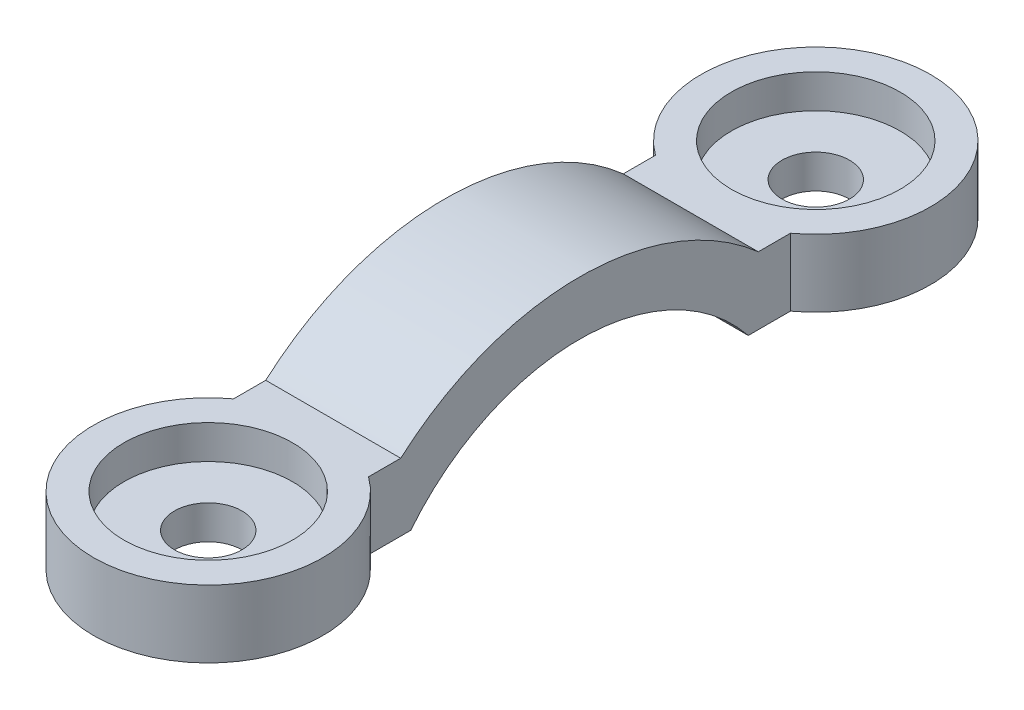
SolidWorks part; units mm, degrees
ref_plane "Plan de face" through (0, 0, 0) normal (0, 0, 1) x (1, 0, 0)
ref_plane "Plan de dessus" through (0, 0, 0) normal (0, 1, 0) x (1, 0, 0)
ref_plane "Plan de droite" through (0, 0, 0) normal (1, 0, 0) x (0, 0, -1)
sketch "Esquisse2" plane through (0, 0, 0) normal (1, 0, 0) x (0, 0, -1)
  line L0 (-16.7178, 10) -> (20.1552, 10) construction
  line L1 (-14.3614, 10) -> (-27.5028, 10)
  line L2 (-27.5028, 10) -> (-27.5028, 15)
  line L3 (-27.5028, 15) -> (-13.2439, 15)
  line L4 (14.3614, 10) -> (22.5028, 10)
  line L5 (27.5028, 15) -> (27.5028, 10)
  line L6 (27.5028, 15) -> (13.2439, 15)
  line L7 (27.5028, 10) -> (22.5028, 10)
  line L8 (-14.3614, 10) -> (-12.5028, 10)
  line L9 (12.5028, 10) -> (22.5028, 10)
  arc A0 (12.5028, 10) -> (-12.5028, 10) centre (0, 0) ccw
  arc A2 (13.2439, 15) -> (-13.2439, 15) centre (0, 0) ccw
  point P5 (-22.5028, 10)
  point P6 (22.5028, 10)
  point P7 (-12.5028, 10)
  point P8 (12.5028, 10)
  dimension "D1" = 32.02
  dimension "D3" = 10
  dimension "D5" = 5
  dimension "D7" = 4
  dimension "D2" = 10
  dimension "D4" = 10
  dimension "D6" = 5
  dimension "D8" = 5
  dimension "D9" = 5
extrude "BASE" add sketch "Esquisse2" along normal blind 10 contours L6 A2 L3 L2 L1 L8 A0 L9 L4 L7 L5
sketch "Esquisse5" plane through (0, 10, 0) normal (0, -1, 0) x (1, 0, 0)
  line L0 (5, 27.5028) -> (5, 12.5028) construction
  line L1 (10, 27.5028) -> (0, 27.5028) construction
  line L2 (10, 12.5028) -> (0, 12.5028) construction
  line L3 (-3.4429, 0) -> (13.3559, 0) construction
  circle A0 centre (5, 22.5028) radius 2.5
  circle A1 centre (5, -22.5028) radius 2.5
  dimension "D2" = 5
  dimension "D1" = 5
extrude "VIDE ACCES VIS" cut sketch "Esquisse5" against normal through all
sketch "Esquisse6" plane through (0, 15, 0) normal (0, 1, 0) x (1, 0, 0)
  circle A0 centre (5, 22.5028) radius 8.5
  circle A1 centre (5, -22.5028) radius 8.5
  circle A2 centre (5, 22.5028) radius 2.5874
  circle A3 centre (5, -22.5028) radius 2.5
  dimension "D1" = 17
  dimension "D2" = 17
extrude "BOSS VIS" add sketch "Esquisse6" against normal up to surface (5 mm away) up to face at (5, 10, -20.0028)
sketch "Esquisse7" plane through (0, 15, 0) normal (0, 1, 0) x (1, 0, 0)
  circle A0 centre (5, 22.5028) radius 6.25
  circle A1 centre (5, -22.5028) radius 6.25
  dimension "D1" = 12.5
  dimension "D2" = 12.5
extrude "VIDE ECROU" cut sketch "Esquisse7" against normal blind 2.5
